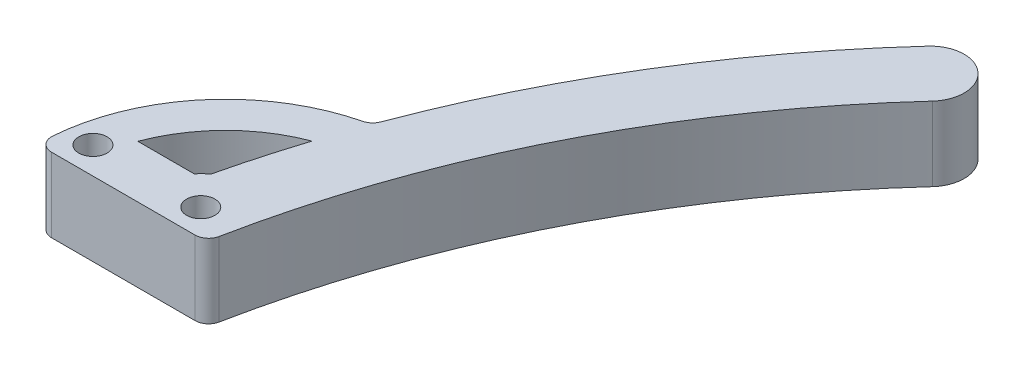
SolidWorks part; units mm, degrees
ref_plane "Front" through (0, 0, 0) normal (0, 0, 1) x (1, 0, 0)
ref_plane "Top" through (0, 0, 0) normal (0, 1, 0) x (1, 0, 0)
ref_plane "Right" through (0, 0, 0) normal (1, 0, 0) x (0, 0, -1)
sketch "Sketch1" plane through (0, 0, 0) normal (0, 1, 0) x (1, 0, 0)
  line L0 (-162.2427, 34.7972) -> (-153.8706, 34.7972)
  line L8 (-169.3167, 27) -> (-144.2855, 27)
  circle A18 centre (-149.1011, 31) radius 2.1
  circle A19 centre (-165.1011, 31) radius 2.1
  arc A25 (-147.0896, 54.2932) -> (-169.3167, 27) centre (-141.4461, 27) ccw
  arc A26 (-149.3386, 47.7607) -> (-162.2427, 34.7972) centre (-141.4461, 27) ccw
  arc A28 (-152.6035, 35.99) -> (-153.8706, 34.7972) centre (-149.1011, 31) ccw
  arc A33 (-108.4373, 98.9376) -> (-115.8245, 105.6777) centre (-112.1309, 102.3077) ccw
  arc A34 (-108.4373, 98.9376) -> (-144.2855, 27) centre (0, 0) ccw
  arc A35 (-115.8245, 105.6777) -> (-147.0896, 54.2932) centre (0, 0) ccw
  arc A36 (-149.3386, 47.7607) -> (-152.6035, 35.99) centre (0, 0) ccw
extrude "Boss-Extrude1" add sketch "Sketch1" along normal blind 11
fillet "Fillet1" radius 2 3 edges at (-147.0896, 5.5, -54.2932) (-169.3167, 5.5, -27) (-144.2855, 5.5, -27)
